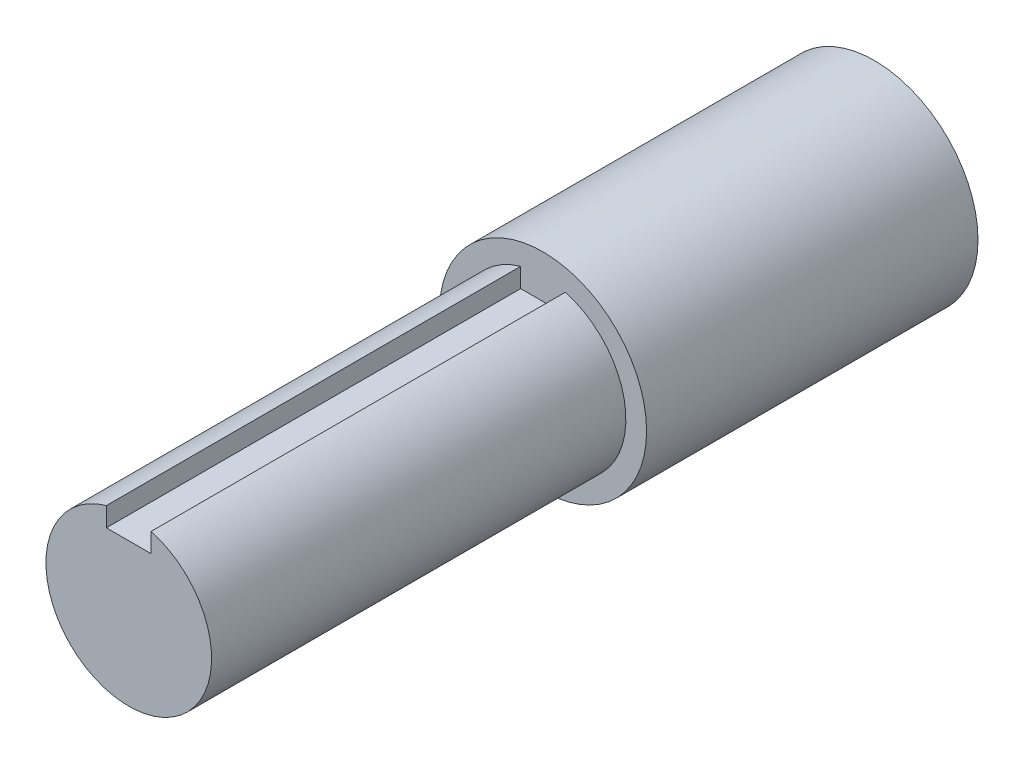
SolidWorks part; units mm, degrees
material "1060 Alloy"
ref_plane "Front Plane" through (0, 0, 0) normal (0, 0, 1) x (1, 0, 0)
ref_plane "Top Plane" through (0, 0, 0) normal (0, 1, 0) x (1, 0, 0)
ref_plane "Right Plane" through (0, 0, 0) normal (1, 0, 0) x (0, 0, -1)
sketch "Sketch1" plane through (0, 0, 0) normal (0, 0, 1) x (1, 0, 0)
  circle A0 centre (0, 0) radius 7.9375
  dimension "D1" = 15.875
extrude "Boss-Extrude1" add sketch "Sketch1" along normal blind 57.15
sketch "Sketch2" plane through (0, 0, 0) normal (0, 0, -1) x (-1, 0, 0)
  circle A0 centre (0, 0) radius 3.8989
  dimension "D1" = 7.7978
extrude "Cut-Extrude1" cut sketch "Sketch2" against normal blind 31.75
sketch "Sketch3" plane through (0, 0, 57.15) normal (0, 0, 1) x (1, 0, 0)
  line L1 (-1.7145, 4.6355) -> (1.7145, 4.6355)
  line L2 (-1.7145, 4.6355) -> (-1.7145, 6.1142)
  line L4 (1.7145, 4.6355) -> (1.7145, 6.1142)
  arc A0 (-1.7145, 6.1142) -> (1.7145, 6.1142) centre (0, 0) ccw
  circle A1 centre (0, 0) radius 8.001
  point P4 (0, 6.35)
  dimension "D1" = 16.002
  dimension "D2" = 12.7
extrude "Cut-Extrude2" cut sketch "Sketch3" against normal blind 31.75
